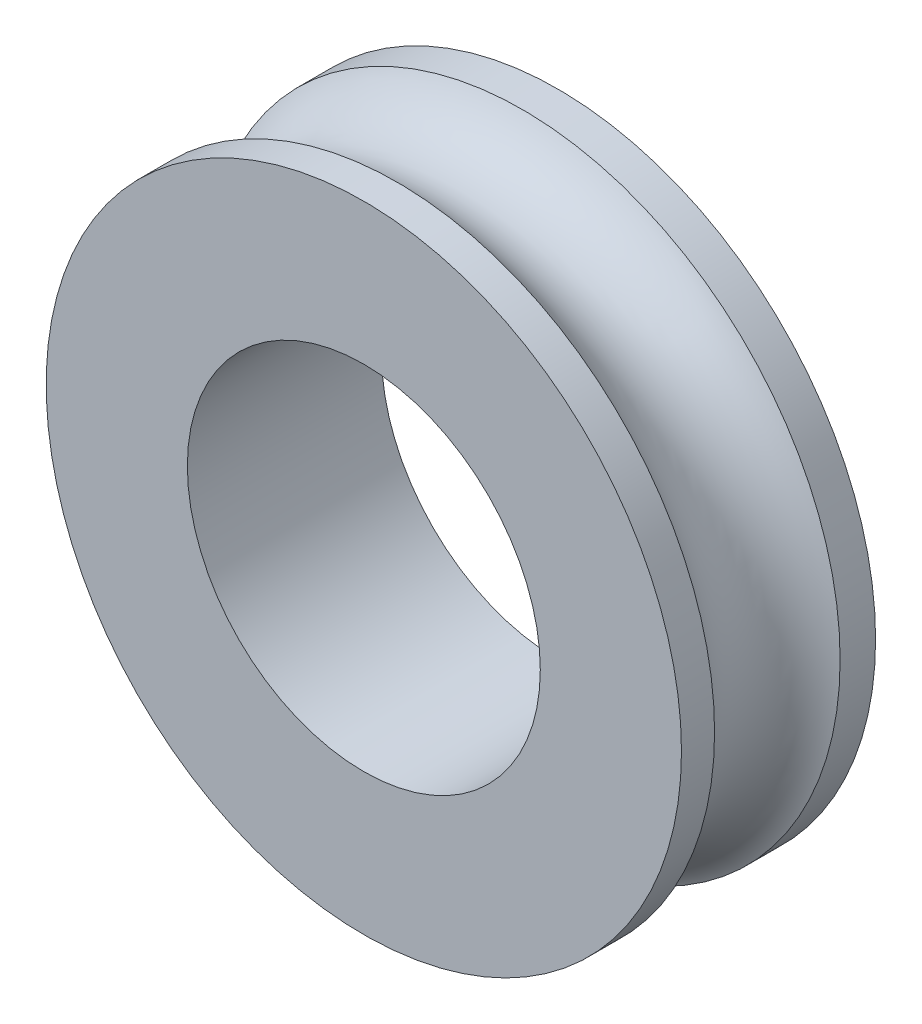
SolidWorks part; units mm, degrees
ref_plane "前视基准面" through (0, 0, 0) normal (0, 0, 1) x (1, 0, 0)
ref_plane "上视基准面" through (0, 0, 0) normal (0, 1, 0) x (1, 0, 0)
ref_plane "右视基准面" through (0, 0, 0) normal (1, 0, 0) x (0, 0, -1)
sketch "草图1" plane through (0, 0, 0) normal (0, 0, 1) x (1, 0, 0)
  circle A0 centre (0, 0) radius 5
  circle A1 centre (0, 0) radius 9
extrude "凸台-拉伸1" add sketch "草图1" along normal blind 5.5
sketch "草图2" plane through (0, 0, 0) normal (0, 1, 0) x (1, 0, 0)
  circle A0 centre (9.9108, -2.7835) radius 1.9983
sketch "草图3" plane through (0, 0, 0) normal (0, 0, -1) x (-1, 0, 0)
  circle A0 centre (0, 0) radius 9.9067
sweep "切除-扫描1" cut profiles "草图2" path "草图3"
equation "\"mm\"=5.5"
